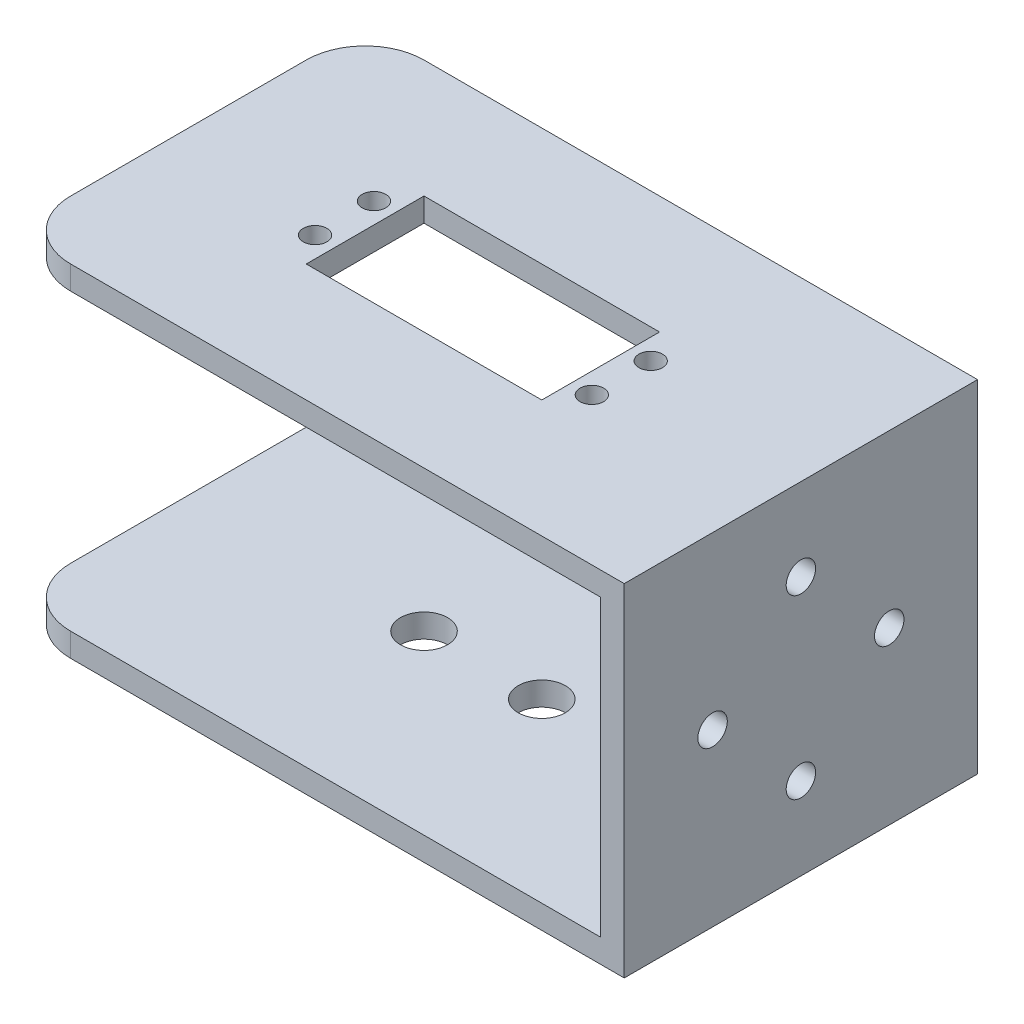
SolidWorks part; units mm, degrees
ref_plane "Ön Düzlem" through (0, 0, 0) normal (0, 0, 1) x (1, 0, 0)
ref_plane "Üst Düzlem" through (0, 0, 0) normal (0, 1, 0) x (1, 0, 0)
ref_plane "Sağ Düzlem" through (0, 0, 0) normal (1, 0, 0) x (0, 0, -1)
sketch "Çizim1" plane through (0, 0, 0) normal (0, 0, 1) x (1, 0, 0)
  line L0 (0, 0) -> (100, 0)
  line L1 (100, 0) -> (100, 50)
  line L2 (100, 50) -> (0, 50)
  dimension "D1" = 50
  dimension "D2" = 100
  dimension "D3" = 100
extrude "Ekstrüzyon-İnce1" add sketch "Çizim1" along normal blind 60 thin
fillet "Radyus1" radius 10 4 edges at (0, -2, 60) (0, -2, 0) (0, 52, 0) (0, 52, 60)
sketch "Çizim3" plane through (104, 0, 0) normal (1, 0, 0) x (0, 0, -1)
  line L0 (-60, -4) -> (-60, 54) construction
  line L1 (0, -4) -> (0, 54) construction
  circle A0 centre (-30, 40) radius 2.5
  circle A1 centre (-30, 10) radius 2.5
  circle A2 centre (-15, 25) radius 2.5
  circle A3 centre (-45, 25) radius 2.5
  dimension "D1" = 5
  dimension "D2" = 30
  dimension "D3" = 5
  dimension "D4" = 15
  dimension "D5" = 15
  dimension "D6" = 30
extrude "Kes-Ekstrüzyon3" cut sketch "Çizim3" against normal up to next
sketch "Çizim4" plane through (0, 54, 0) normal (0, 1, 0) x (1, 0, 0)
  line L0 (104, 0) -> (10, 0) construction
  line L1 (30, -20) -> (70, -20)
  line L2 (30, -20) -> (30, -40)
  line L3 (30, -40) -> (70, -40)
  line L4 (70, -20) -> (70, -40)
  line L6 (0, -50) -> (0, -10) construction
  line L9 (50, -20) -> (50, -40) construction
  circle A0 centre (26.5, -25) radius 2
  circle A1 centre (26.5, -35) radius 2
  circle A2 centre (73.5, -35) radius 2
  circle A3 centre (73.5, -25) radius 2
  dimension "D7" = 4
  dimension "D5" = 4
  dimension "D6" = 10
  dimension "D1" = 40
  dimension "D2" = 20
  dimension "D3" = 20
  dimension "D4" = 30
extrude "Kes-Ekstrüzyon4" cut sketch "Çizim4" against normal up to next
sketch "Çizim5" plane through (0, -4, 0) normal (0, -1, 0) x (1, 0, 0)
  line L0 (0, 50) -> (0, 10) construction
  line L1 (40, 30) -> (60, 30) construction
  line L2 (10, 60) -> (104, 60) construction
  circle A0 centre (40, 30) radius 4
  circle A1 centre (60, 30) radius 4
  dimension "D2" = 8
  dimension "D1" = 40
  dimension "D3" = 30
  dimension "D5" = 8
  dimension "D4" = 20
extrude "Kes-Ekstrüzyon5" cut sketch "Çizim5" against normal up to next
